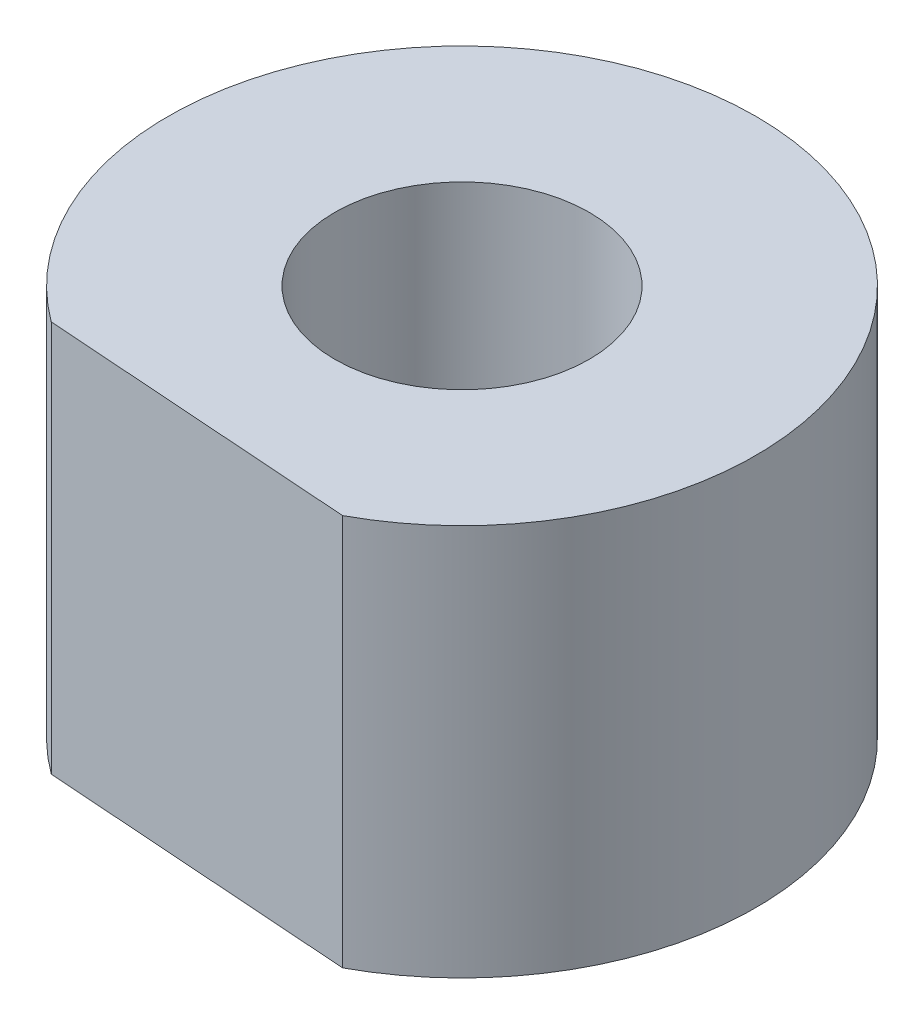
SolidWorks part; units mm, degrees
ref_plane "Front Plane" through (0, 0, 0) normal (0, 0, 1) x (1, 0, 0)
ref_plane "Top Plane" through (0, 0, 0) normal (0, 1, 0) x (1, 0, 0)
ref_plane "Right Plane" through (0, 0, 0) normal (1, 0, 0) x (0, 0, -1)
sketch "Sketch1" plane through (0, 0, 0) normal (0, 1, 0) x (1, 0, 0)
  line L0 (-4.4458, -6.0403) -> (3.5542, -6.6043)
  circle A0 centre (0, 0) radius 3.25
  arc A1 (3.5542, -6.6043) -> (-4.4458, -6.0403) centre (0, 0) ccw
  dimension "D1" = 6.5
  dimension "D2" = 15
  dimension "D3" = 8
extrude "Boss-Extrude1" add sketch "Sketch1" along normal blind 10
